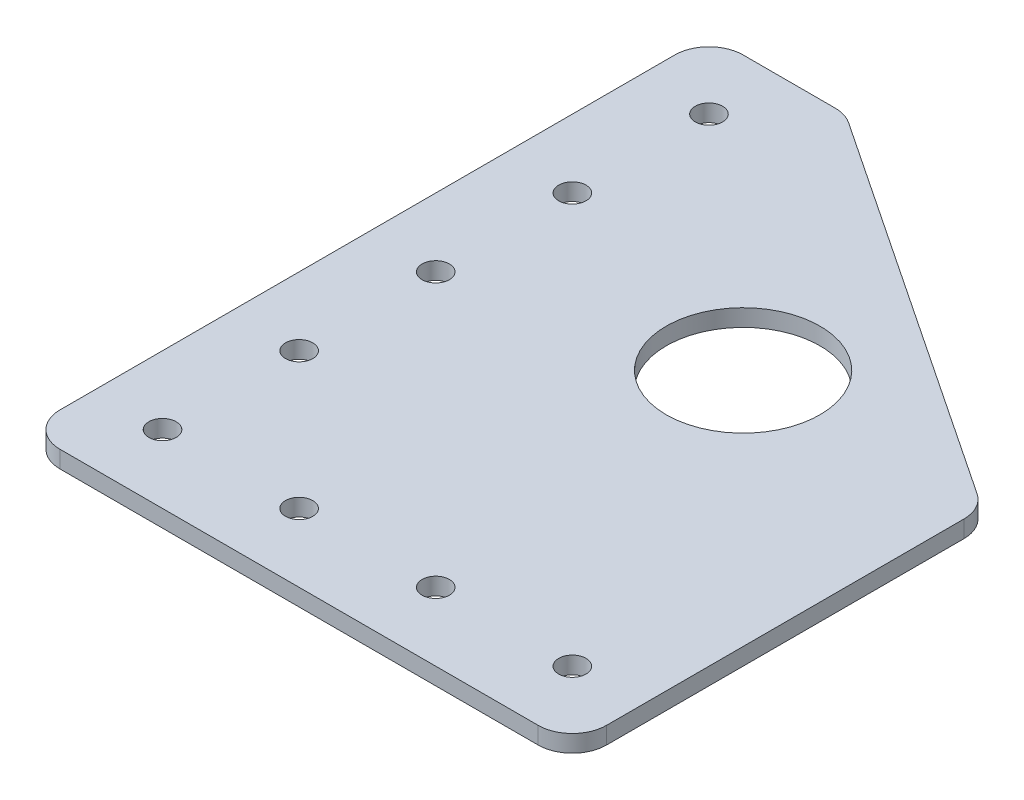
SolidWorks part; units mm, degrees
ref_plane "Front Plane" through (0, 0, 0) normal (0, 0, 1) x (1, 0, 0)
ref_plane "Top Plane" through (0, 0, 0) normal (0, 1, 0) x (1, 0, 0)
ref_plane "Right Plane" through (0, 0, 0) normal (1, 0, 0) x (0, 0, -1)
sketch "Sketch1" plane through (0, 0, 0) normal (0, 1, 0) x (1, 0, 0)
  line L0 (0, 6.35) -> (0, 120.65)
  line L1 (6.35, 127) -> (23.4774, 127)
  line L2 (26.9997, 125.9335) -> (98.7723, 78.0851)
  line L3 (101.6, 72.8016) -> (101.6, 6.35)
  line L4 (95.25, 0) -> (6.35, 0)
  line L5 (88.9, 12.7) -> (63.5, 12.7) construction
  line L6 (12.7, 12.7) -> (12.7, 38.1) construction
  circle A0 centre (88.9, 12.7) radius 2.54
  circle A1 centre (63.5, 12.7) radius 2.54
  circle A2 centre (38.1, 12.7) radius 2.54
  circle A3 centre (12.7, 12.7) radius 2.54
  circle A4 centre (12.7, 38.1) radius 2.54
  circle A5 centre (12.7, 63.5) radius 2.54
  circle A6 centre (12.7, 88.9) radius 2.54
  circle A7 centre (12.7, 114.3) radius 2.54
  circle A8 centre (57.15, 76.2) radius 14.2875
  arc A9 (98.7723, 78.0851) -> (101.6, 72.8016) centre (95.25, 72.8016) cw
  arc A10 (101.6, 6.35) -> (95.25, 0) centre (95.25, 6.35) cw
  arc A11 (0, 6.35) -> (6.35, 0) centre (6.35, 6.35) ccw
  arc A12 (23.4774, 127) -> (26.9997, 125.9335) centre (23.4774, 120.65) cw
  arc A13 (0, 120.65) -> (6.35, 127) centre (6.35, 120.65) cw
  point P28 (0, 0)
  point P31 (101.6, 76.2)
  point P34 (101.6, 0)
  point P37 (0, 0)
  point P40 (25.4, 127)
  point P43 (0, 127)
  dimension "D5" = 5.08
  dimension "D6" = 12.7
  dimension "D7" = 12.7
  dimension "D12" = 28.575
  dimension "D13" = 44.45
  dimension "D14" = 6.35
  dimension "D15" = 6.35
  dimension "D16" = 6.35
  dimension "D17" = 6.35
  dimension "D18" = 6.35
  dimension "D1" = 127
  dimension "D2" = 25.4
  dimension "D3" = 76.2
  dimension "D4" = 101.6
  dimension "D9" = 25.4
  dimension "D11" = 25.4
  dimension "D8" = 4
  dimension "D10" = 5
extrude "Boss-Extrude1" add sketch "Sketch1" along normal blind 3.175
